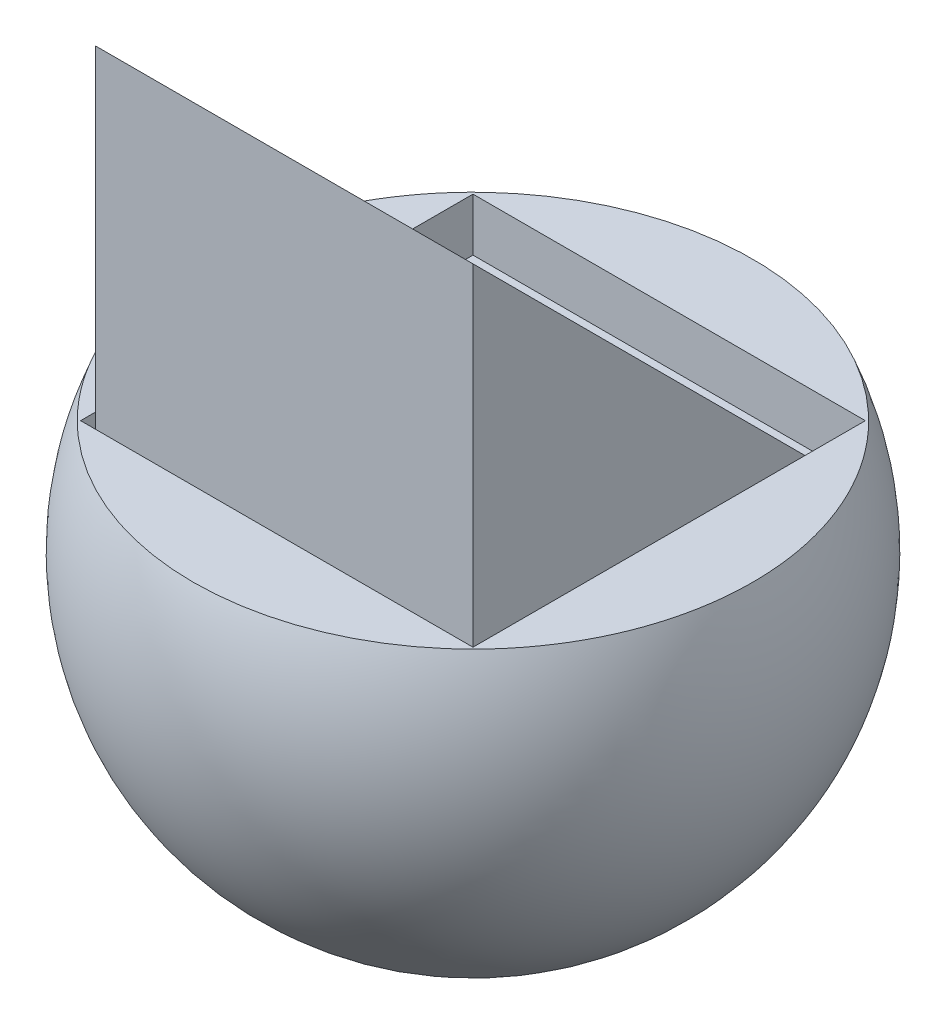
SolidWorks part; units mm, degrees
ref_plane "前视基准面" through (0, 0, 0) normal (0, 0, 1) x (1, 0, 0)
ref_plane "上视基准面" through (0, 0, 0) normal (0, 1, 0) x (1, 0, 0)
ref_plane "右视基准面" through (0, 0, 0) normal (1, 0, 0) x (0, 0, -1)
sketch "草图1" plane through (0, 0, 0) normal (0, 1, 0) x (1, 0, 0)
  line L0 (-4, 0) -> (4, 0)
  arc A0 (-4, 0) -> (4, 0) centre (0, 0) ccw
  dimension "D1" = 8
revolve "旋转1" add sketch "草图1" angle 360 about L0
ref_plane "基准面1" through (0, 2, 0) normal (0, 1, 0) x (1, 0, 0)
sketch "草图2" plane through (0, 2, 0) normal (0, 1, 0) x (1, 0, 0)
  line L1 (4, -4) -> (-4, -4)
  line L2 (4, -4) -> (4, 4)
  line L3 (4, 4) -> (-4, 4)
  line L4 (-4, -4) -> (-4, 4)
  line L5 (4, -4) -> (-4, 4) construction
  line L6 (4, 4) -> (-4, -4) construction
  circle A0 centre (0, 0) radius 4 construction
  point P0 (0, 0)
extrude "切除-拉伸1" cut sketch "草图2" along normal blind 10
sketch "草图6" plane through (0, 2, 0) normal (0, 1, 0) x (1, 0, 0)
  circle A0 centre (0, 0) radius 1.5
  dimension "D1" = 3
extrude "切除-拉伸2" cut sketch "草图6" against normal through all
sketch "草图8" plane through (0, 2, 0) normal (0, 1, 0) x (1, 0, 0)
  line L1 (2.5, -2.5) -> (-2.5, -2.5)
  line L2 (2.5, -2.5) -> (2.5, 2.5)
  line L3 (2.5, 2.5) -> (-2.5, 2.5)
  line L4 (-2.5, -2.5) -> (-2.5, 2.5)
  line L5 (2.5, -2.5) -> (-2.5, 2.5) construction
  line L6 (2.5, 2.5) -> (-2.5, -2.5) construction
  point P0 (0, 0)
  dimension "D1" = 5
  dimension "D2" = 5
extrude "切除-拉伸3" cut sketch "草图8" against normal blind 1.2
sketch "草图7" plane through (0, 0, 0) normal (1, 0, 0) x (0, 0, -1)
  line L0 (-2.5, 5.8) -> (-2.5, 0.8)
  line L1 (-2.5, 0.8) -> (2.5, 0.8)
  line L2 (2.5, 0.8) -> (-2.5, 5.8)
  line L4 (2.5, 0.8) -> (-2.5, 0.8) construction
  point P2 (0, 3.3)
  dimension "D1" = 5
  dimension "D2" = 45
extrude "凸台-拉伸4" add sketch "草图7" along normal mid plane 5 separate body
sketch "草图9" plane through (0, 1.65, -1.65) normal (0, 0.7071, -0.7071) x (1, 0, 0)
  line L0 (2.5, 1.2021) -> (2.5, -5.869) construction
  point P0 (0, -2.3335)
  dimension "D1" = 2.5
sketch "草图11" plane through (0, 2, 0) normal (0, 1, 0) x (1, 0, 0)
  line L1 (2.5, -2.5) -> (-2.5, -2.5)
  line L2 (2.5, -2.5) -> (2.5, 2.5)
  line L3 (2.5, 2.5) -> (-2.5, 2.5)
  line L4 (-2.5, -2.5) -> (-2.5, 2.5)
  line L5 (2.5, -2.5) -> (-2.5, 2.5) construction
  line L6 (2.5, 2.5) -> (-2.5, -2.5) construction
  circle A0 centre (0, 0) radius 3.9961
extrude "切除-拉伸5" cut sketch "草图11" against normal blind 0.5
sketch "草图12" plane through (0, 0, 0) normal (1, 0, 0) x (0, 0, -1)
  line L1 (0.5, -0.5) -> (-0.5, -0.5)
  line L2 (0.5, -0.5) -> (0.5, 0.5)
  line L3 (0.5, 0.5) -> (-0.5, 0.5)
  line L4 (-0.5, -0.5) -> (-0.5, 0.5)
  line L5 (0.5, -0.5) -> (-0.5, 0.5) construction
  line L6 (0.5, 0.5) -> (-0.5, -0.5) construction
  point P0 (0, 0)
  dimension "D1" = 1
  dimension "D2" = 1
extrude "切除-拉伸6" cut sketch "草图12" against normal offset from surface (4.9497 mm away) 1
sketch "草图13" plane through (0, 1.5, 0) normal (0, 1, 0) x (1, 0, 0)
  line L4 (-2.5, 2.5) -> (-2.5, -2.5)
  line L5 (-2.5, -2.5) -> (2.5, -2.5)
  line L6 (2.5, -2.5) -> (2.5, 2.5)
  line L7 (2.5, 2.5) -> (-2.5, 2.5)
  line L8 (-2.5, 2.5) -> (-2.5, -2.5)
  line L9 (-2.5, -2.5) -> (2.5, -2.5)
  line L10 (2.5, -2.5) -> (2.5, 2.5)
  line L11 (2.5, 2.5) -> (-2.5, 2.5)
  dimension "D1" = 0
extrude "切除-拉伸-薄壁1" cut sketch "草图13" against normal up to surface (0.7 mm away) thin
